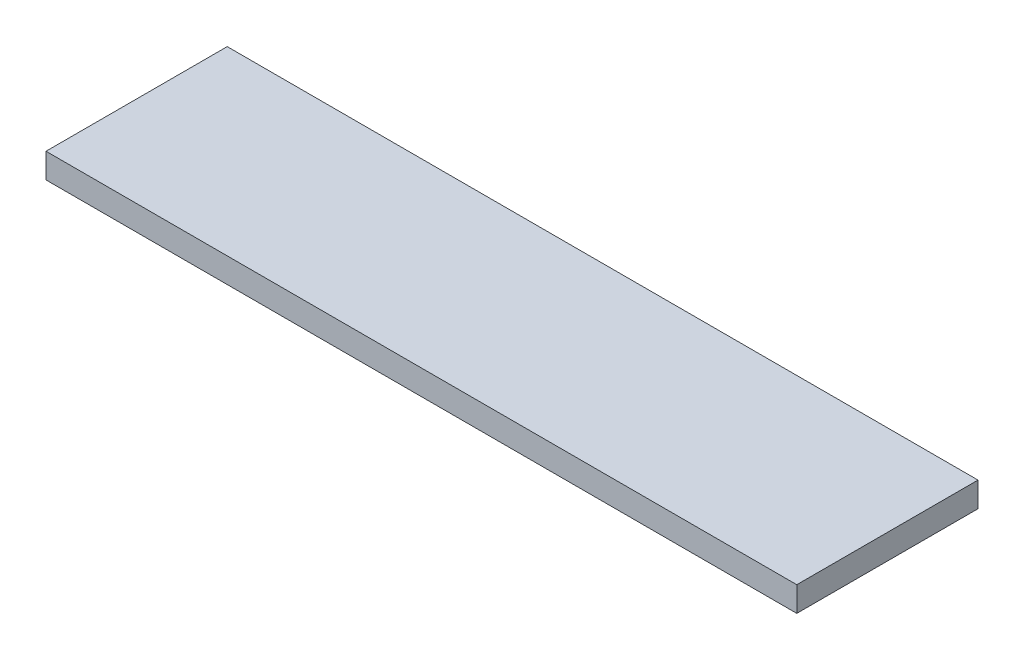
SolidWorks part; units mm, degrees
ref_plane "Front Plane" through (0, 0, 0) normal (0, 0, 1) x (1, 0, 0)
ref_plane "Top Plane" through (0, 0, 0) normal (0, 1, 0) x (1, 0, 0)
ref_plane "Right Plane" through (0, 0, 0) normal (1, 0, 0) x (0, 0, -1)
sketch "Sketch1" plane through (0, 0, 0) normal (0, 1, 0) x (1, 0, 0)
  line L1 (-145, -35) -> (145, -35)
  line L2 (-145, -35) -> (-145, 35)
  line L3 (-145, 35) -> (145, 35)
  line L4 (145, -35) -> (145, 35)
  line L5 (-145, -35) -> (145, 35) construction
  line L6 (-145, 35) -> (145, -35) construction
  point P0 (0, 0)
  dimension "D1" = 70
  dimension "D2" = 290
extrude "Boss-Extrude1" add sketch "Sketch1" along normal blind 9.6
